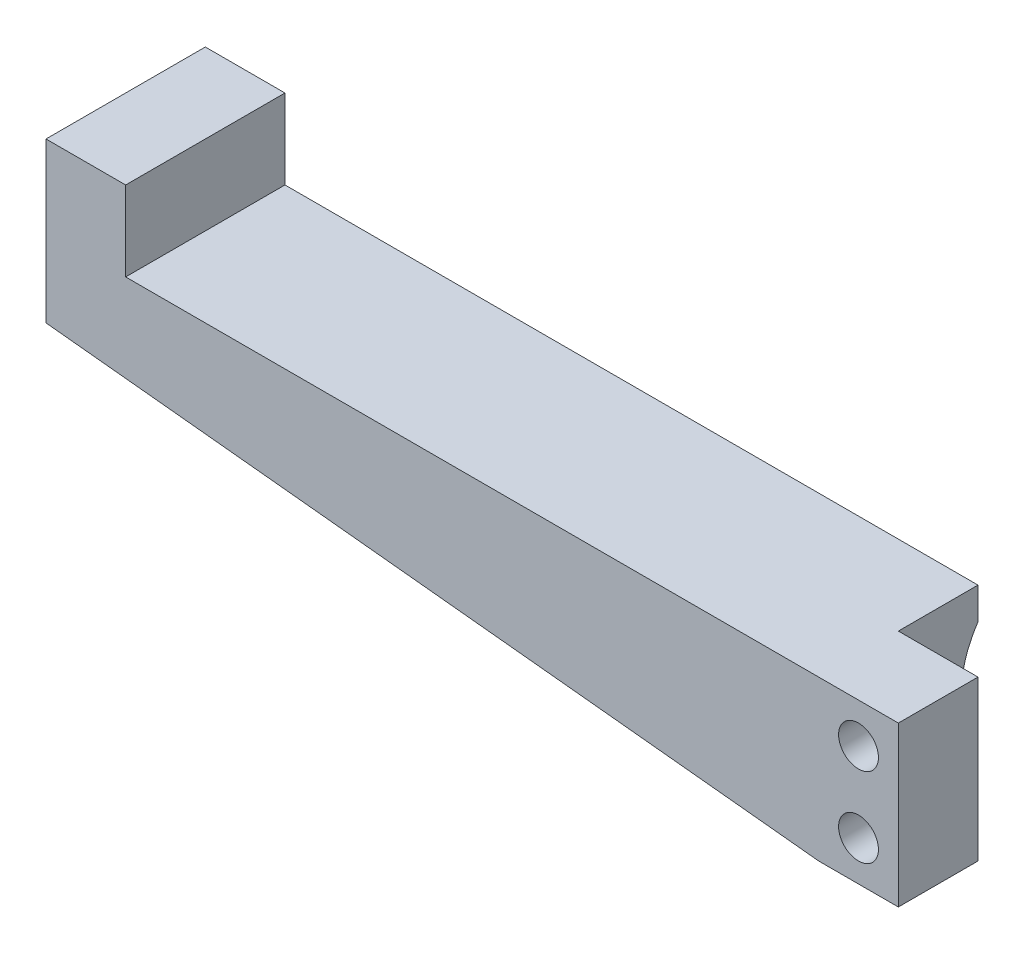
SolidWorks part; units mm, degrees
ref_plane "Plan de face" through (0, 0, 0) normal (0, 0, 1) x (1, 0, 0)
ref_plane "Plan de dessus" through (0, 0, 0) normal (0, 1, 0) x (1, 0, 0)
ref_plane "Plan de droite" through (0, 0, 0) normal (1, 0, 0) x (0, 0, -1)
sketch "Esquisse1" plane through (0, 0, 0) normal (0, 0, 1) x (1, 0, 0)
  line L0 (-102, 0) -> (-5, -10)
  line L1 (-5, -10) -> (5, -10)
  line L3 (-5, 10) -> (5, 10)
  line L4 (5, -10) -> (5, 10)
  line L5 (-5, -10) -> (5, 10) construction
  line L6 (-5, 10) -> (5, -10) construction
  line L7 (-5, 10) -> (-92, 10)
  line L10 (-102, 10) -> (-102, 0)
  line L12 (-102, 10) -> (-102, 20)
  line L13 (-102, 20) -> (-92, 20)
  line L14 (-92, 10) -> (-92, 20)
  circle A0 centre (0, 5) radius 2.5
  circle A1 centre (0, -5) radius 2.5
  point P0 (0, 0)
  dimension "D2" = 5
  dimension "D6" = 5
  dimension "D1" = 20
  dimension "D3" = 10
  dimension "D4" = 5
  dimension "D5" = 5
  dimension "D7" = 97
  dimension "D8" = 10
  dimension "D9" = 10
  dimension "D10" = 10
extrude "Boss.-Extru.1" add sketch "Esquisse1" along normal blind 20
sketch "Esquisse3" plane through (0, 0, 0) normal (0, 0, -1) x (-1, 0, 0)
  line L1 (-5, 10) -> (5, 10)
  line L2 (-5, 10) -> (-5, -10)
  line L3 (-5, -10) -> (5, -10)
  line L4 (5, 10) -> (5, -10)
extrude "Enlèv. mat.-Extru.2" cut sketch "Esquisse3" against normal blind 10
sketch "Esquisse4" plane through (-102, 0, 0) normal (-1, 0, 0) x (0, 0, 1)
  line L0 (20, 0) -> (0, 0) construction
  line L1 (0, 20) -> (0, 0) construction
  line L2 (0, 6) -> (0, -6)
  spline S0 degree 2 poles (0, 6) (4, 0) (0, -6) knots 0 0 0 1 1 1
  point P0 (2, 0)
  point P1 (0, 6)
  point P4 (0, -6)
  dimension "D1" = 2
  dimension "D2" = 6
extrude "Enlèv. mat.-Extru.3" cut sketch "Esquisse4" against normal up to surface (97 mm away) up to face at (-5, 0, 5)
